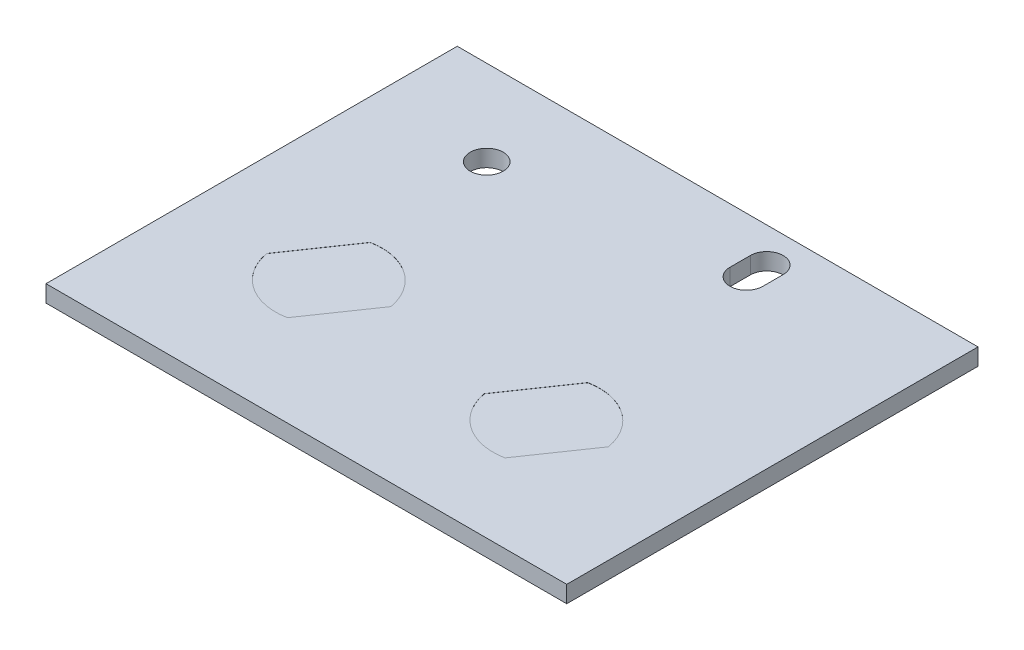
SolidWorks part; units mm, degrees
ref_plane "Plan de face" through (0, 0, 0) normal (0, 0, 1) x (1, 0, 0)
ref_plane "Plan de dessus" through (0, 0, 0) normal (0, 1, 0) x (1, 0, 0)
ref_plane "Plan de droite" through (0, 0, 0) normal (1, 0, 0) x (0, 0, -1)
sketch "Esquisse1" plane through (0, 0, 0) normal (0, 1, 0) x (1, 0, 0)
  line L0 (-18.55, 14.65) -> (18.55, 14.65)
  line L1 (18.55, 14.65) -> (18.55, -14.65)
  line L2 (18.55, -14.65) -> (-18.55, -14.65)
  line L3 (-18.55, -14.65) -> (-18.55, 14.65)
  line L4 (-18.55, 14.65) -> (18.55, -14.65) construction
  line L5 (-18.55, -14.65) -> (18.55, 14.65) construction
  line L6 (5.975, 12.175) -> (5.975, 10.725) construction
  line L7 (7.15, 12.175) -> (7.15, 10.725)
  line L8 (4.8, 12.175) -> (4.8, 10.725)
  arc A0 (7.15, 12.175) -> (4.8, 12.175) centre (5.975, 12.175) ccw
  arc A1 (4.8, 10.725) -> (7.15, 10.725) centre (5.975, 10.725) ccw
  circle A2 centre (-10.375, 8.575) radius 1.175
  point P2 (0, 0)
  point P8 (5.975, 11.45)
  point P13 (5.975, 13.35)
  point P14 (5.975, 9.55)
  point P17 (-10.375, 9.75)
  point P18 (-11.55, 8.575)
  dimension "D5" = 2.35
  dimension "D1" = 37.1
  dimension "D2" = 29.3
  dimension "D3" = 2.35
  dimension "D4" = 3.8
  dimension "D6" = 11.4
  dimension "D7" = 1.3
  dimension "D8" = 4.9
  dimension "D9" = 7
extrude "Boss.-Extru.1" add sketch "Esquisse1" along normal blind 1.2
sketch "Esquisse2" plane through (0, 1.2, 0) normal (0, 1, 0) x (1, 0, 0)
  line L0 (-12.55, -4.9236) -> (-9.55, -0.5544)
  line L1 (-7.851, -8.15) -> (-4.851, -3.7808)
  line L2 (-9.55, -0.5544) -> (-4.851, -3.7808) construction
  line L3 (-12.55, -4.9236) -> (-7.851, -8.15) construction
  line L4 (-18.55, -14.65) -> (18.55, -14.65) construction
  line L5 (-18.55, 14.65) -> (-18.55, -14.65) construction
  line L6 (3.851, -5.8241) -> (6.851, -1.4549)
  line L7 (8.55, -9.0505) -> (11.55, -4.6813)
  line L9 (6.851, -1.4549) -> (11.55, -4.6813) construction
  line L10 (3.851, -5.8241) -> (8.55, -9.0505) construction
  line L11 (18.55, -14.65) -> (18.55, 14.65) construction
  arc A0 (-9.55, -0.5544) -> (-4.851, -3.7808) centre (-8.7766, -4.463) cw
  arc A1 (-12.55, -4.9236) -> (-7.851, -8.15) centre (-8.6245, -4.2414) ccw
  arc A2 (6.851, -1.4549) -> (11.55, -4.6813) centre (7.6245, -5.3635) cw
  arc A3 (3.851, -5.8241) -> (8.55, -9.0505) centre (7.7766, -5.1419) ccw
  point P6 (-10.8798, -7.526)
  point P7 (-6.5213, -1.1783)
  point P18 (5.5213, -8.4266)
  point P19 (9.8798, -2.0789)
  dimension "D1" = 7.7
  dimension "D2" = 5.7
  dimension "D3" = 5.3
  dimension "D4" = 3
  dimension "D5" = 6.5
  dimension "D6" = 6
  dimension "D7" = 5.5995
  dimension "D8" = 5.7
  dimension "D9" = 10
  dimension "D10" = 5.3
  dimension "D11" = 7.7
  dimension "D12" = 3
extrude "Enlèv. mat.-Extru.1" cut sketch "Esquisse2" against normal blind 0.01
